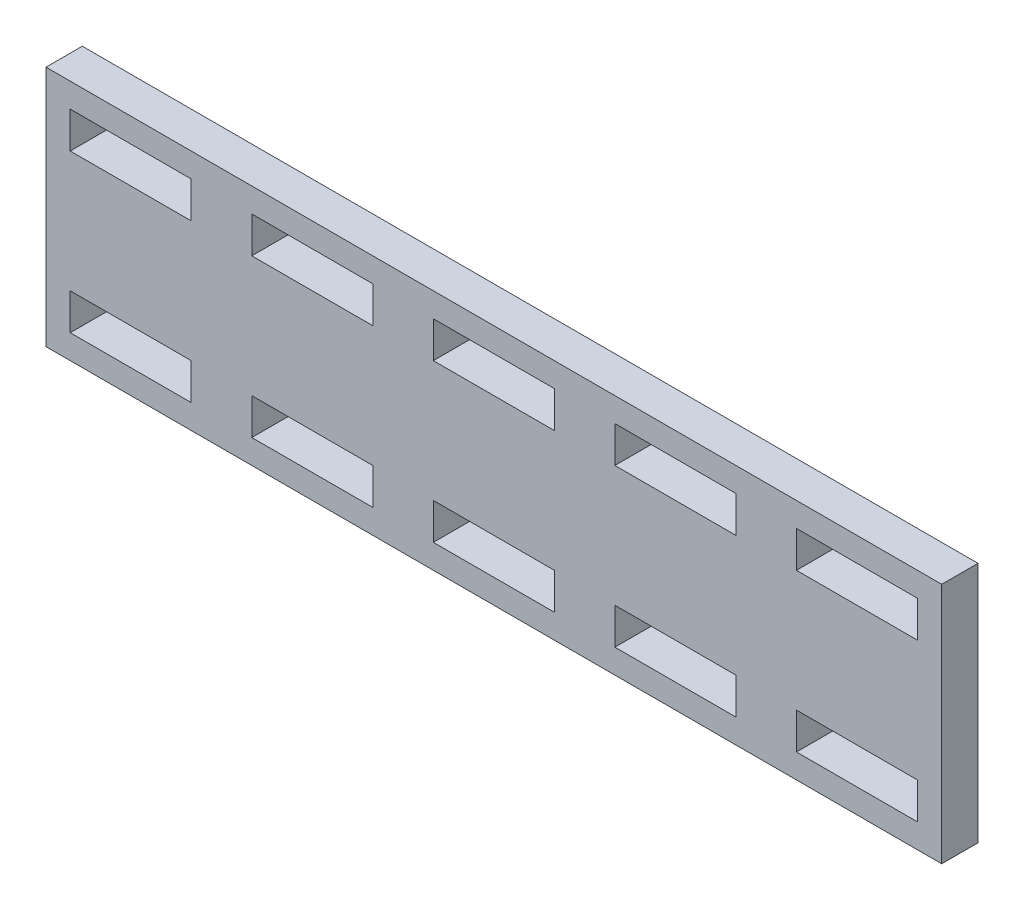
SolidWorks part; units mm, degrees
material "Thornel Mat VMA"
ref_plane "前视基准面" through (0, 0, 0) normal (0, 0, 1) x (1, 0, 0)
ref_plane "上视基准面" through (0, 0, 0) normal (0, 1, 0) x (1, 0, 0)
ref_plane "右视基准面" through (0, 0, 0) normal (1, 0, 0) x (0, 0, -1)
sketch "草图1" plane through (0, 0, 0) normal (0, 0, 1) x (1, 0, 0)
  line L0 (-20, 5) -> (-20, 8)
  line L2 (-37, 5) -> (-37, -5)
  line L4 (37, 5) -> (37, -5)
  line L5 (-37, 5) -> (37, -5) construction
  line L6 (-37, -5) -> (37, 5) construction
  line L7 (-35, 5) -> (-25, 5)
  line L8 (-35, 5) -> (-35, 8)
  line L9 (-35, 8) -> (-25, 8)
  line L10 (-25, 5) -> (-25, 8)
  line L11 (-20, 5) -> (-10, 5)
  line L12 (-10, 5) -> (-10, 8)
  line L13 (-20, 8) -> (-10, 8)
  line L14 (-5, 5) -> (-5, 8)
  line L15 (-5, 5) -> (5, 5)
  line L16 (5, 5) -> (5, 8)
  line L17 (-5, 8) -> (5, 8)
  line L18 (10, 5) -> (10, 8)
  line L19 (10, 5) -> (20, 5)
  line L20 (20, 5) -> (20, 8)
  line L21 (10, 8) -> (20, 8)
  line L22 (25, 5) -> (25, 8)
  line L23 (25, 5) -> (35, 5)
  line L24 (35, 5) -> (35, 8)
  line L25 (25, 8) -> (35, 8)
  line L26 (1.65, 0) -> (-1.65, 0) construction
  line L27 (25, -5) -> (35, -5)
  line L28 (35, -5) -> (35, -8)
  line L29 (25, -8) -> (35, -8)
  line L30 (25, -5) -> (25, -8)
  line L31 (10, -5) -> (20, -5)
  line L32 (20, -5) -> (20, -8)
  line L33 (10, -8) -> (20, -8)
  line L34 (10, -5) -> (10, -8)
  line L35 (-5, -5) -> (5, -5)
  line L36 (5, -5) -> (5, -8)
  line L37 (-5, -8) -> (5, -8)
  line L38 (-5, -5) -> (-5, -8)
  line L39 (-20, -5) -> (-10, -5)
  line L40 (-10, -5) -> (-10, -8)
  line L41 (-20, -8) -> (-10, -8)
  line L42 (-20, -5) -> (-20, -8)
  line L43 (-35, -8) -> (-25, -8)
  line L44 (-25, -5) -> (-25, -8)
  line L45 (-35, -5) -> (-25, -5)
  line L46 (-35, -5) -> (-35, -8)
  line L47 (-37, 5) -> (-37, 10)
  line L48 (-37, 10) -> (37, 10)
  line L49 (37, 10) -> (37, 5)
  line L50 (37, -10) -> (37, -5)
  line L51 (-37, -10) -> (37, -10)
  line L52 (-37, -5) -> (-37, -10)
  point P0 (0, 0)
  dimension "D1" = 74
  dimension "D2" = 10
  dimension "D3" = 10
  dimension "D4" = 3
  dimension "D5" = 2
  dimension "D6" = 5
extrude "凸台-拉伸3" add sketch "草图1" along normal blind 3
